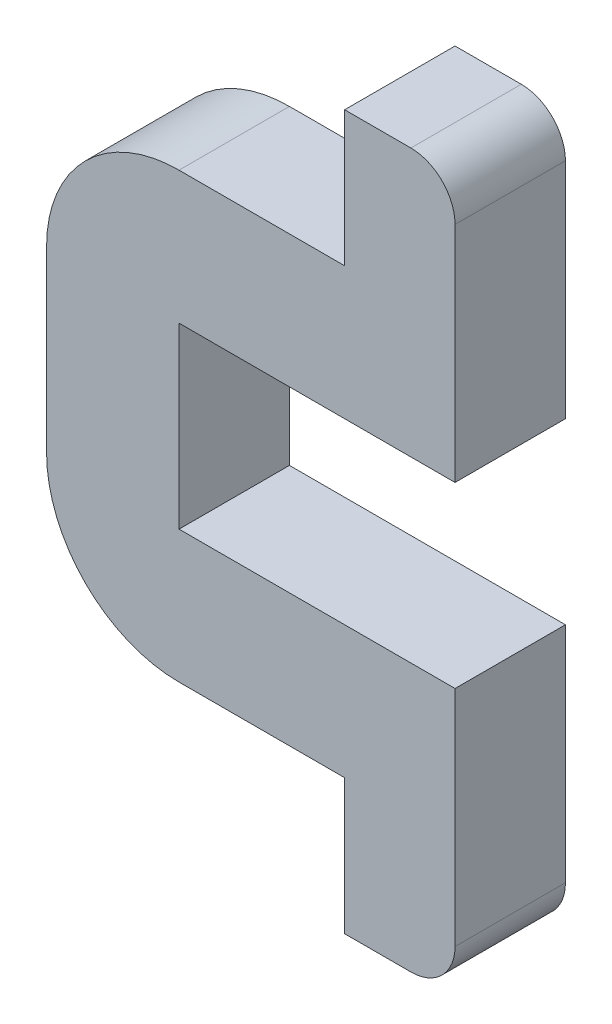
SolidWorks part; units mm, degrees
material "PBT General Purpose"
ref_plane "Front Plane" through (0, 0, 0) normal (0, 0, 1) x (1, 0, 0)
ref_plane "Top Plane" through (0, 0, 0) normal (0, 1, 0) x (1, 0, 0)
ref_plane "Right Plane" through (0, 0, 0) normal (1, 0, 0) x (0, 0, -1)
sketch "frame_outline" plane through (0, 0, 0) normal (0, 0, 1) x (1, 0, 0)
  line L0 (0, 0) -> (-0.625, 0)
  line L1 (-0.625, 0) -> (-0.625, 0.404)
  line L2 (-0.625, 0.404) -> (0, 0.404)
  line L3 (0, 0.404) -> (0, 1.01)
  line L71 (0, 1.01) -> (-0.25, 1.01)
  line L90 (-0.25, 1.01) -> (-0.25, 0.704)
  line L91 (-0.25, 0.704) -> (-0.925, 0.704)
  line L93 (-0.925, 0.704) -> (-0.925, -0.3)
  line L95 (-0.925, -0.3) -> (-0.25, -0.3)
  line L96 (-0.25, -0.3) -> (-0.25, -0.606)
  line L97 (-0.25, -0.606) -> (0, -0.606)
  line L98 (0, -0.606) -> (0, 0)
  dimension "D3" = 0.404
  dimension "D4" = 0.625
  dimension "D5" = 0.25
  dimension "D6" = 0.3
  dimension "D7" = 0.306
  dimension "D8" = 0.3
extrude "Boss-Extrude1" add sketch "frame_outline" along normal mid plane 0.25
fillet "Fillet1" radius 0.3 2 edges at (-0.925, -0.3, 0) (-0.925, 0.704, 0)
fillet "Fillet2" radius 0.1 2 edges at (0, 1.01, 0) (0, -0.606, 0)
equation "\"t\"= 0.25'thickness of the sheets"
equation "\"t_cf\"= 0.115'thickness of single carbon fiber layer"
equation "\"t_kapton\"= 0.025'thickness of single Kapton flex layer"
equation "\"t_fr4\"= 0.1'thickness of FR4 with copper layer"
equation "\"joint_flex\"= 0.1'Width of flextures gap"
equation "\"joint_flex_eff\"= 0.02'Width of flecture after castelation"
equation "\"joint_fold\"= 0.2'Width of folding joints for 90deg fold"
equation "\"gap_tolerance\"= 0.002'Width to have interfecence fit between carbon fiber inserts"
equation "\"assemble_angle\"= 90'Angle of assembly parts"
equation "\"D1@Boss-Extrude1\"=\"t\""
equation "\"D3@frame_outline\"=0.4+\"gap_tolerance\"*2"
equation "\"D4@frame_outline\"=\"t\"*2.5"
equation "\"D5@frame_outline\"=\"t\""
equation "\"D7@frame_outline\"=0.3+\"gap_tolerance\"*3"
equation "\"link_lift\"= 0.5'Actuation linkage amplification for the lift motion"
equation "\"link_swing\"= 0.45'Actuation linkage amplification for the swing motion"
